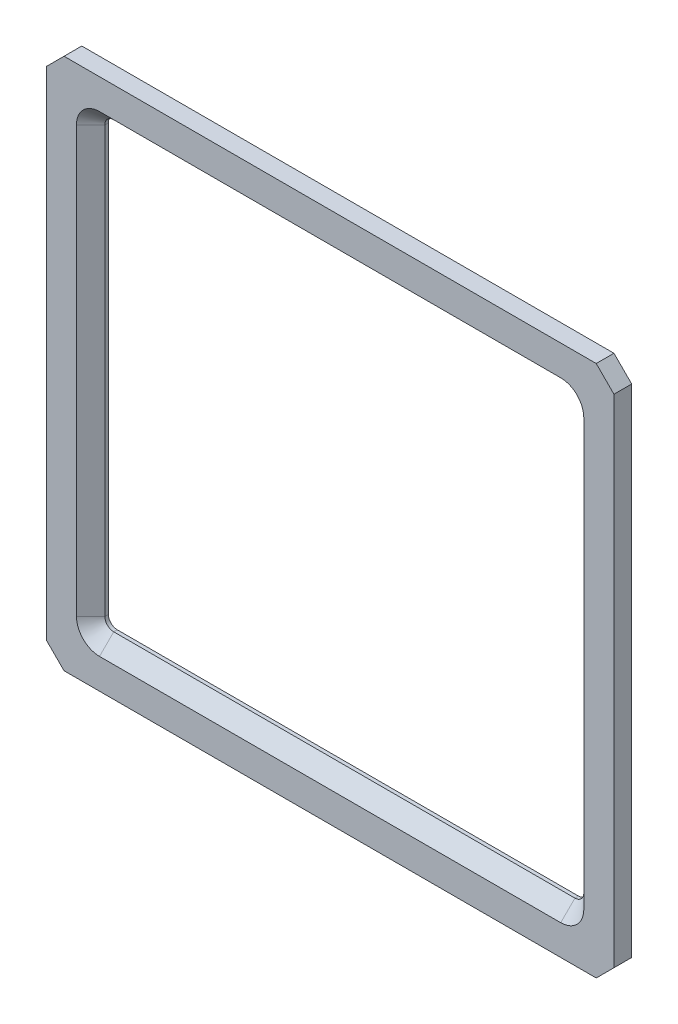
SolidWorks part; units mm, degrees
ref_plane "前视基准面" through (0, 0, 0) normal (0, 0, 1) x (1, 0, 0)
ref_plane "上视基准面" through (0, 0, 0) normal (0, 1, 0) x (1, 0, 0)
ref_plane "右视基准面" through (0, 0, 0) normal (1, 0, 0) x (0, 0, -1)
sketch "草图1" plane through (0, 0, 0) normal (0, 0, 1) x (1, 0, 0)
  line L1 (-160, 150) -> (160, 150)
  line L2 (-160, 150) -> (-160, -150)
  line L3 (-160, -150) -> (160, -150)
  line L4 (160, 150) -> (160, -150)
  line L5 (-160, 150) -> (160, -150) construction
  line L6 (-160, -150) -> (160, 150) construction
  point P0 (0, 0)
  dimension "D1" = 320
  dimension "D2" = 300
extrude "凸台-拉伸1" add sketch "草图1" along normal blind 10
chamfer "倒角1" distance 10 angle 45 4 edges at (-160, -150, 5) (160, -150, 5) (-160, 150, 5) (160, 150, 5)
sketch "草图2" plane through (0, 0, 10) normal (0, 0, 1) x (1, 0, 0)
  line L1 (-130, 125) -> (130, 125)
  line L2 (-135, 120) -> (-135, -120)
  line L3 (-130, -125) -> (130, -125)
  line L4 (135, 120) -> (135, -120)
  line L5 (-135, 125) -> (135, -125) construction
  line L6 (-135, -125) -> (135, 125) construction
  arc A0 (-135, -120) -> (-130, -125) centre (-130, -120) ccw
  arc A1 (130, -125) -> (135, -120) centre (130, -120) ccw
  arc A2 (130, 125) -> (135, 120) centre (130, 120) cw
  arc A3 (-130, 125) -> (-135, 120) centre (-130, 120) ccw
  point P0 (0, 0)
  dimension "D3" = 5
  dimension "D1" = 270
  dimension "D2" = 250
extrude "切除-拉伸1" cut sketch "草图2" against normal up to next
chamfer "倒角2" distance 8 angle 45 8 edges at (0, -125, 10) (133.5355, -123.5355, 10) (-133.5355, -123.5355, 10) (135, 0, 10) (-135, 0, 10) (133.5355, 123.5355, 10) (-133.5355, 123.5355, 10) (0, 125, 10)
